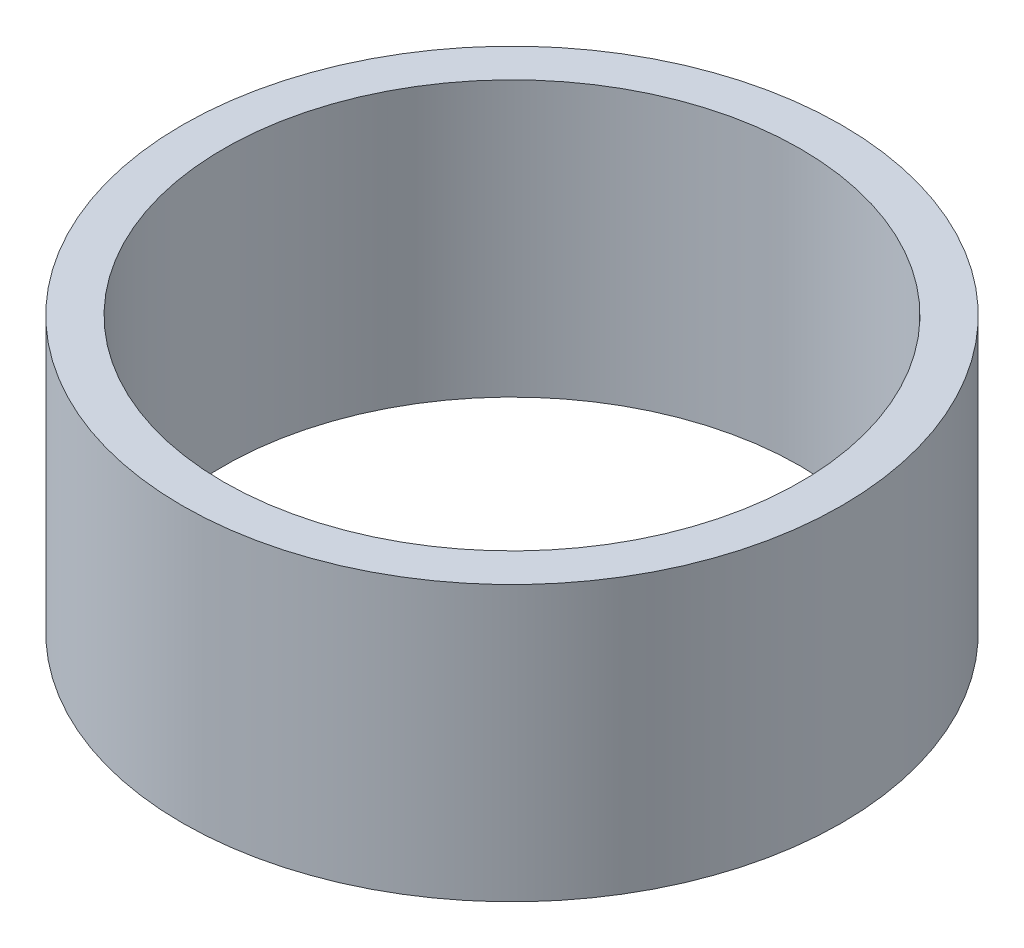
SolidWorks part; units mm, degrees
ref_plane "前视基准面" through (0, 0, 0) normal (0, 0, 1) x (1, 0, 0)
ref_plane "上视基准面" through (0, 0, 0) normal (0, 1, 0) x (1, 0, 0)
ref_plane "右视基准面" through (0, 0, 0) normal (1, 0, 0) x (0, 0, -1)
sketch "草图1" plane through (0, 0, 0) normal (0, 1, 0) x (1, 0, 0)
  circle A0 centre (0, 0) radius 5.25
  circle A1 centre (0, 0) radius 6
  dimension "D1" = 10.5
  dimension "D2" = 12
extrude "凸台-拉伸1" add sketch "草图1" along normal blind 5
